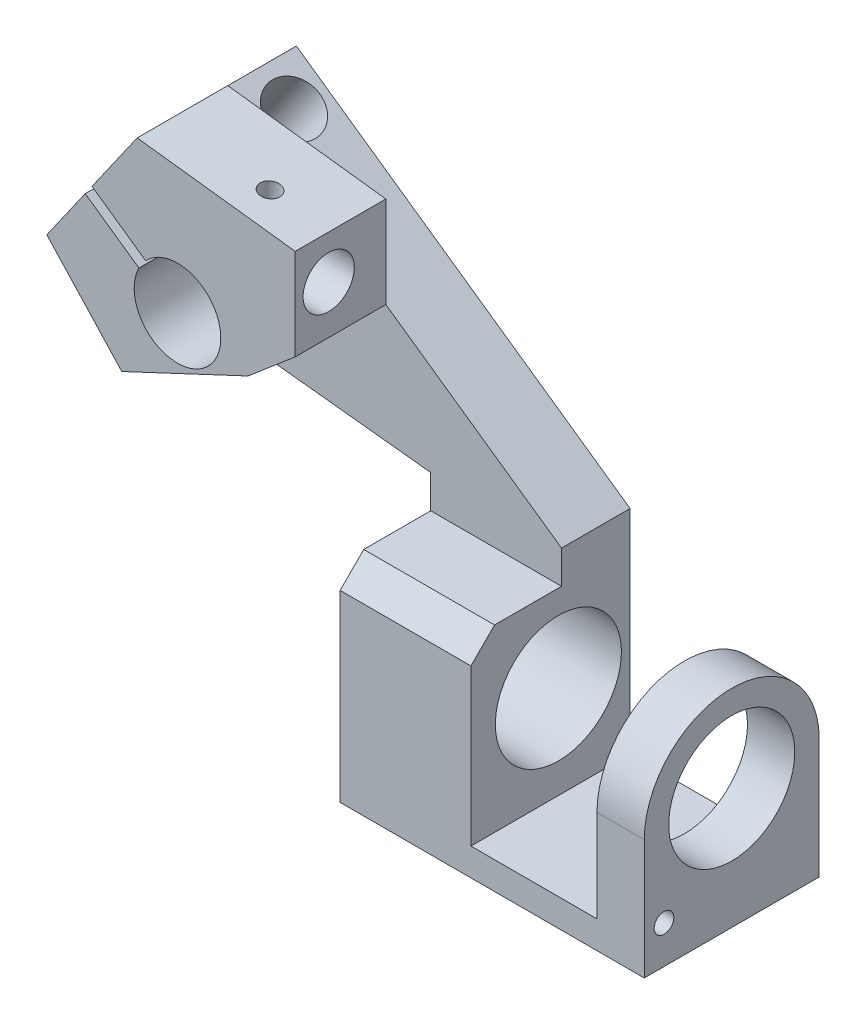
SolidWorks part; units mm, degrees
other "Pincement"
material "Alliage 2014"
ref_plane "Plan de face" through (0, 0, 0) normal (0, 0, 1) x (1, 0, 0)
ref_plane "Plan de dessus" through (0, 0, 0) normal (0, 1, 0) x (1, 0, 0)
ref_plane "Plan de droite" through (0, 0, 0) normal (1, 0, 0) x (0, 0, -1)
sketch "Esquisse1" plane through (0, 0, 0) normal (0, 0, 1) x (1, 0, 0)
  line L0 (-23.7131, 25.8326) -> (-23.7131, -4.6674)
  line L1 (-23.7131, 25.8326) -> (-42.0761, 27.8205)
  line L3 (-42.0761, 27.8205) -> (-51.4215, 28.8322)
  line L4 (-51.4215, 28.8322) -> (-60.9348, 39.1034)
  line L5 (-60.9348, 39.1034) -> (-49.4633, 55.4865)
  line L6 (-49.4633, 55.4865) -> (-29.4112, 53.0459)
  line L7 (-29.4112, 53.0459) -> (-29.4112, 41.4459)
  line L8 (-29.4112, 41.4459) -> (-7.1131, 25.8326)
  line L9 (-7.1131, 25.8326) -> (-7.1131, 21.6326)
  line L10 (-23.7131, -4.6674) -> (14.8869, -4.6674)
  line L11 (14.8869, -4.6674) -> (14.8869, -1.1674)
  line L12 (14.8869, -1.1674) -> (-7.1131, -1.1674)
  line L13 (-7.1131, -1.1674) -> (-7.1131, 21.6326)
  dimension "D1" = 22
  dimension "D2" = 20.2
  dimension "D3" = 11.6
  dimension "D4" = 20
  dimension "D5" = 14
  dimension "D6" = 9.4
  dimension "D7" = 3.5
  dimension "D8" = 16.6
  dimension "D9" = 22.8
  dimension "D10" = 51.7
  dimension "D11" = 4.2
  dimension "D12" = 235
extrude "Extrusion1" add sketch "Esquisse1" along normal blind 20.2
sketch "Esquisse2" plane through (0, 0, 0) normal (0, 0, -1) x (-1, 0, 0)
  line L0 (49.4633, 55.4865) -> (29.4112, 41.4459)
  line L1 (29.4112, 41.4459) -> (29.4112, 53.0459)
  line L2 (29.4112, 53.0459) -> (49.4633, 55.4865)
  line L3 (29.4112, 41.4459) -> (29.4112, 53.0459) construction
  line L4 (29.4112, 53.0459) -> (49.4633, 55.4865) construction
extrude "Extrusion2" cut sketch "Esquisse2" against normal blind 8.7
sketch "Esquisse3" plane through (0, 0, 20.2) normal (0, 0, 1) x (1, 0, 0)
  line L0 (-29.4112, 41.4459) -> (-35.3979, 36.3511)
  line L1 (-35.3979, 36.3511) -> (-51.4215, 28.8322)
  line L2 (-51.4215, 28.8322) -> (-23.7131, 25.8326)
  line L3 (-7.1131, 25.8326) -> (-7.1131, 21.6326)
  line L4 (-7.1131, 21.6326) -> (-23.7131, 21.6326)
  line L5 (-23.7131, 25.8326) -> (-23.7131, -4.6674) construction
  line L6 (-23.7131, 21.6326) -> (-23.7131, 25.8326)
  line L8 (-7.1131, 25.8326) -> (-29.4112, 41.4459)
  line L9 (-51.4215, 28.8322) -> (-23.7131, 25.8326) construction
  line L10 (-7.1131, -1.1674) -> (-7.1131, 25.8326) construction
  line L11 (-23.7131, -4.6674) -> (14.8869, -4.6674) construction
  dimension "D1" = 17.7
  dimension "D2" = 26.3
extrude "Extrusion3" cut sketch "Esquisse3" against normal up to vertex (11.5 mm away)
sketch "Esquisse5" plane through (0, 0, 20.2) normal (0, 0, 1) x (1, 0, 0)
  line L0 (-56.0594, 46.0662) -> (-55.199, 47.295)
  line L1 (-56.0594, 46.0662) -> (-49.2442, 41.2942)
  line L2 (-55.199, 47.295) -> (-48.3838, 42.5229)
  line L3 (-49.2442, 41.2942) -> (-48.3838, 42.5229)
  line L4 (-49.4633, 55.4865) -> (-60.9348, 39.1034) construction
  dimension "D1" = 1.5
  dimension "D2" = 10
extrude "Extrusion5" cut sketch "Esquisse5" against normal through all
sketch "Esquisse7" plane through (0, 0, 0) normal (0, 0, -1) x (-1, 0, 0)
  circle A0 centre (44.3507, 38.7833) radius 5.5
extrude "Extrusion7" cut sketch "Esquisse7" against normal through all
chamfer "Chanfrein1" distance 3 angle 45 1 edges at (-15.4131, 21.6326, 20.2)
sketch "Esquisse11" plane through (0, 0, 0) normal (0, 0, -1) x (-1, 0, 0)
  line L0 (23.7131, -4.6674) -> (-14.8869, -4.6674) construction
  line L1 (-14.8869, -1.1674) -> (-8.8869, -1.1674)
  line L2 (-14.8869, -1.1674) -> (-14.8869, -4.6674)
  line L3 (-14.8869, -4.6674) -> (-8.8869, -4.6674)
  line L4 (-8.8869, -1.1674) -> (-8.8869, -4.6674)
  dimension "D1" = 16
extrude "Extrusion10" add sketch "Esquisse11" along normal blind 2
sketch "Esquisse12" plane through (0, -1.1674, 0) normal (0, 1, 0) x (-1, 0, 0)
  line L1 (-8.8869, -2) -> (-14.8869, -2)
  line L2 (-8.8869, -2) -> (-8.8869, 20.2)
  line L3 (-8.8869, 20.2) -> (-14.8869, 20.2)
  line L4 (-14.8869, -2) -> (-14.8869, 20.2)
extrude "Extrusion11" add sketch "Esquisse12" along normal blind 11.7
sketch "Esquisse13" plane through (14.8869, 0, 0) normal (1, 0, 0) x (0, 0, -1)
  line L0 (-20.2, 10.5326) -> (2, 10.5326) construction
  line L1 (-20.2, 10.5326) -> (2, 10.5326)
  line L2 (-20.2, -4.6674) -> (-20.2, 10.5326) construction
  line L3 (2, 10.5326) -> (2, -4.6674) construction
  arc A0 (-20.2, 10.5326) -> (2, 10.5326) centre (-9.1, 10.5326) cw
extrude "Extrusion12" add sketch "Esquisse13" against normal up to vertex
hole_wizard "Dégagement M61" positions "Esquisse3D4" profile "Esquisse18" hole size "M6" standard "ISO"
sketch3d "Esquisse3D4"
  line L0 (-49.4633, 55.4865, 8.7) -> (-49.4633, 55.4865, 0) construction
  line L1 (-7.1131, 25.8326, 0) -> (-49.4633, 55.4865, 0) construction
  point P0 (-45.4703, 52.6906, 4.2939)
  dimension "D1" = 4.8745
  dimension "D2" = 4.2939
sketch "Esquisse18" plane through (-45.4703, 52.6906, 4.2939) normal (0, 0, 1) x (-0.8192, 0.5736, 0)
  line L0 (0, 0) -> (0, 10)
  line L1 (0, 10) -> (3.3, 10)
  line L2 (3.3, 10) -> (3.3, 0)
  line L5 (3.3, 0) -> (0, 0)
  line L11 (0, -6.35) -> (0, 107.95) construction
  dimension "Diamètre du perçage jusqu'au prochain" = 6.6
  dimension "Profondeur du perçage jusqu'au prochain" = 10
hole_wizard "Trou taraudé M62" positions "Esquisse3D5" profile "Esquisse20" tap size "M6" standard "ISO" end condition through all
sketch3d "Esquisse3D5"
  line L0 (-56.0594, 46.0662, 0) -> (-56.0594, 46.0662, 20.2) construction
  line L1 (-56.0594, 46.0662, 0) -> (-49.2442, 41.2942, 0) construction
  point P0 (-52.0668, 43.2706, 4.294)
  dimension "D1" = 4.874
  dimension "D2" = 4.294
sketch "Esquisse20" plane through (-52.0668, 43.2706, 4.294) normal (0, 0, 1) x (-0.8192, 0.5736, 0)
  line L0 (0, 0) -> (0, 44.355)
  line L1 (0, 44.355) -> (2.5, 44.355)
  line L2 (2.5, 44.355) -> (2.5, 0)
  line L5 (2.5, 0) -> (0, 0)
  line L11 (0, -6.35) -> (0, 107.95) construction
  dimension "Diamètre du trou pour taraudage jusqu'au prochain" = 5
  dimension "Profondeur du trou pour taraudage jusqu'au prochain" = 44.355
cosmetic thread "Filetage de perçage3" parameters "D2"=6
sketch "Esquisse21" plane through (14.8869, 0, 0) normal (1, 0, 0) x (0, 0, -1)
  circle A0 centre (-9.1, 10.6326) radius 8
  arc A1 (2, 10.5326) -> (-20.2, 10.5326) centre (-9.1, 10.5326) ccw construction
  point P3 (-9.1, 21.6326)
  dimension "D1" = 11
extrude "Extrusion13" cut sketch "Esquisse21" against normal through all
sketch "Esquisse22" plane through (-29.4112, 0, 0) normal (1, 0, 0) x (0, 0, -1)
  line L0 (-20.2, 41.4459) -> (-20.2, 53.0459) construction
  line L1 (-20.2, 53.0459) -> (-8.7, 53.0459) construction
  circle A0 centre (-15.95, 47.5459) radius 3.25
  dimension "D1" = 4.25
  dimension "D2" = 5.5
extrude "Extrusion14" cut sketch "Esquisse22" against normal through all
hole_wizard "Trou taraudé M31" positions "Esquisse24" profile "Esquisse23" tap size "M3" standard "ISO"
sketch "Esquisse24" plane through (5.9328, 48.7441, 0) normal (0.1208, 0.9927, 0) x (-0.9927, 0.1208, 0)
  line L0 (35.6048, 20.2) -> (55.8048, 20.2) construction
  line L1 (35.6048, 20.2) -> (35.6048, 8.7) construction
  point P0 (43.1048, 15.95)
  dimension "D1" = 4.25
  dimension "D2" = 7.5
sketch "Esquisse23" plane through (-36.8563, 53.9521, 15.95) normal (0, 0, 1) x (-0.9927, 0.1208, 0)
  line L0 (0, 0) -> (0, 5.2511)
  line L1 (0, 5.2511) -> (1.25, 4.5)
  line L2 (1.25, 4.5) -> (1.25, 0)
  line L5 (1.25, 0) -> (0, 0)
  line L10 (0, 5.2511) -> (-1.25, 4.5) construction
  line L11 (0, -6.35) -> (0, 107.95) construction
  dimension "Diamètre du trou pour taraudage" = 2.5
  dimension "Profondeur du trou pour taraudage" = 4.5
  dimension "Angle de pointe" = 118
cosmetic thread "Filetage de perçage4" parameters "D1"=1.3326, "D2"=3
hole_wizard "Trou taraudé M32" positions "Esquisse3D6" profile "Esquisse25" tap size "M3" standard "ISO"
sketch3d "Esquisse3D6"
  line L0 (14.8869, -4.6674, 20.2) -> (14.8869, -4.6674, -2) construction
  line L1 (14.8869, -4.6674, 20.2) -> (14.8869, 10.5326, 20.2) construction
  point P0 (14.8869, 0.1326, 17.7)
  dimension "D1" = 4.8
  dimension "D2" = 2.5
cosmetic thread "Filetage de perçage5" parameters "D1"=6, "D2"=3
sketch "Esquisse25" plane through (14.8869, 0.1326, 17.7) normal (0, 1, 0) x (0, 0, -1)
  line L0 (0, 0) -> (0, 8.2511)
  line L1 (0, 8.2511) -> (1.25, 7.5)
  line L2 (1.25, 7.5) -> (1.25, 0)
  line L5 (1.25, 0) -> (0, 0)
  line L10 (0, 8.2511) -> (-1.25, 7.5) construction
  line L11 (0, -6.35) -> (0, 107.95) construction
  dimension "Diamètre du trou pour taraudage" = 2.5
  dimension "Profondeur du trou pour taraudage" = 7.5
  dimension "Angle de pointe" = 118
